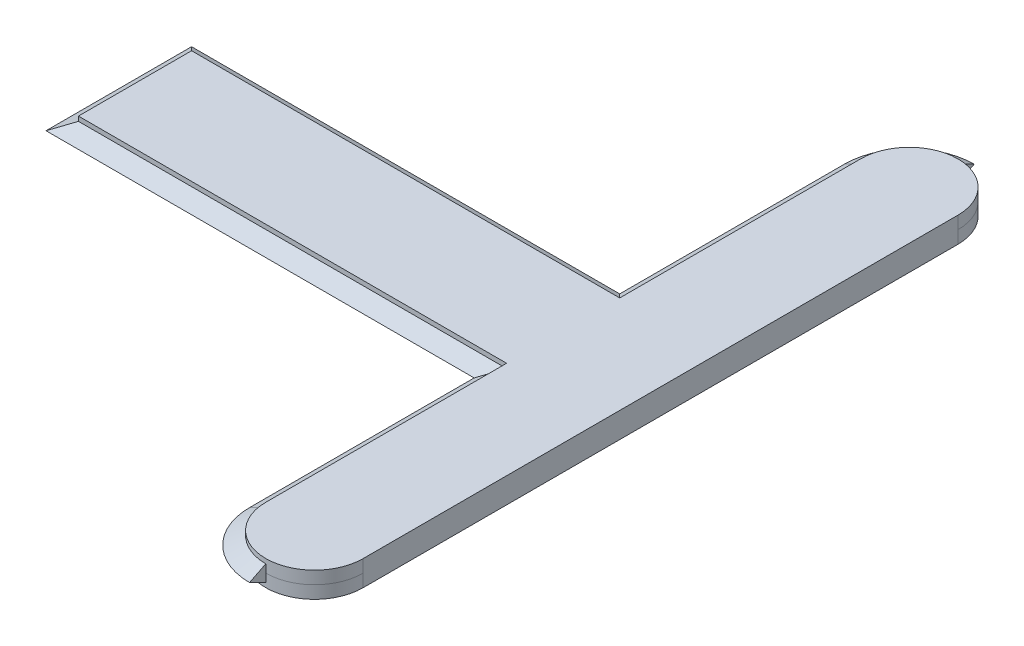
SolidWorks part; units mm, degrees
ref_plane "Front Plane" through (0, 0, 0) normal (0, 0, 1) x (1, 0, 0)
ref_plane "Top Plane" through (0, 0, 0) normal (0, 1, 0) x (1, 0, 0)
ref_plane "Right Plane" through (0, 0, 0) normal (1, 0, 0) x (0, 0, -1)
sketch "Sketch1" plane through (0, 0, 0) normal (0, 1, 0) x (1, 0, 0)
  line L0 (0, -13.4216) -> (101.6, -13.4216)
  line L1 (101.6, -13.4216) -> (101.6, -70.5716)
  line L2 (124.714, -70.5716) -> (124.714, 70.5716)
  line L3 (101.6, 70.5716) -> (101.6, 13.4216)
  line L4 (101.6, 13.4216) -> (0, 13.4216)
  line L5 (0, 13.4216) -> (0, -13.4216)
  arc A0 (101.6, -70.5716) -> (124.714, -70.5716) centre (113.157, -70.5716) ccw
  arc A1 (124.714, 70.5716) -> (101.6, 70.5716) centre (113.157, 70.5716) ccw
  point P12 (0, 0)
extrude "Boss-Extrude1" add sketch "Sketch1" along normal blind 6
sketch "Sketch2" plane through (0, 0, 0) normal (0, 0, 1) x (1, 0, 0)
  line L0 (0, 3) -> (101.6, 3)
  line L1 (0, 6) -> (0, 0) construction
  line L2 (101.6, 6) -> (101.6, 0) construction
split line "Split Line1"
sketch "Sketch3" plane through (0, 0, 0) normal (1, 0, 0) x (0, 0, -1)
  line L0 (82.1286, 3) -> (-82.1286, 3)
  line L1 (82.1286, 0) -> (82.1286, 6) construction
  line L2 (-82.1286, 6) -> (-82.1286, 0) construction
split line "Split Line2"
curve "CompCurve1"
ref_plane "Plane1" through (113.157, 0, 0) normal (1, 0, 0) x (0, 0, -1)
sketch "Sketch4" plane through (113.157, 0, 0) normal (1, 0, 0) x (0, 0, -1)
  line L0 (82.1286, 4.9103) -> (82.1286, 1.0603)
  line L6 (82.1286, 3) -> (82.1286, 6) construction
  line L7 (82.1286, 0) -> (82.1286, 3) construction
  line L8 (82.1286, 4.9103) -> (85.9786, 2.9853)
  line L9 (82.1286, 1.0603) -> (85.9786, 2.9853)
  dimension "D1" = 3.85
  dimension "D2" = 3.85
sweep "Sweep1" add profiles "Sketch4" path "CompCurve1"
